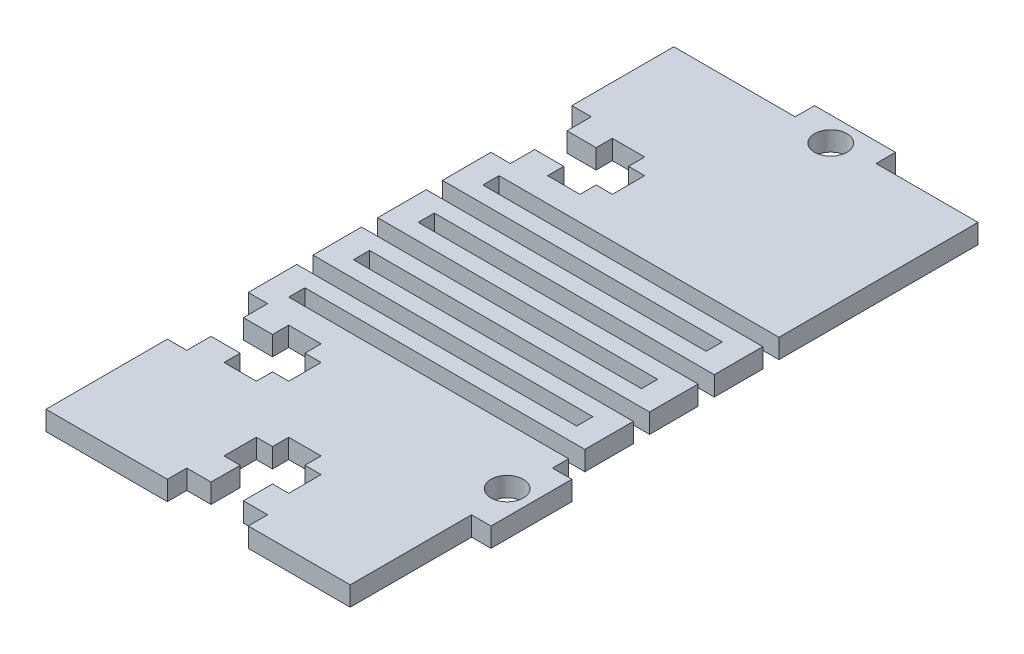
SolidWorks part; units mm, degrees
ref_plane "Front Plane" through (0, 0, 0) normal (0, 0, 1) x (1, 0, 0)
ref_plane "Top Plane" through (0, 0, 0) normal (0, 1, 0) x (1, 0, 0)
ref_plane "Right Plane" through (0, 0, 0) normal (1, 0, 0) x (0, 0, -1)
sketch "Sketch1" plane through (0, 0, 0) normal (0, 1, 0) x (1, 0, 0)
  line L1 (0, 0) -> (50.8, 0)
  line L2 (0, 0) -> (0, 50.8)
  line L3 (0, 50.8) -> (50.8, 50.8)
  line L4 (50.8, 0) -> (50.8, 50.8)
  line L5 (19.05, 50.8) -> (0, 50.8)
  line L6 (19.05, 50.8) -> (19.05, 47.752)
  line L7 (19.05, 47.752) -> (0, 47.752)
  line L8 (0, 50.8) -> (0, 47.752)
  line L9 (31.75, 50.8) -> (50.8, 50.8)
  line L10 (31.75, 50.8) -> (31.75, 47.752)
  line L11 (31.75, 47.752) -> (50.8, 47.752)
  line L12 (50.8, 50.8) -> (50.8, 47.752)
  line L13 (50.8, 50.8) -> (47.752, 50.8)
  line L14 (50.8, 50.8) -> (50.8, 31.75)
  line L15 (50.8, 31.75) -> (47.752, 31.75)
  line L16 (47.752, 50.8) -> (47.752, 31.75)
  line L17 (50.8, 0) -> (47.752, 0)
  line L18 (50.8, 0) -> (50.8, 19.05)
  line L19 (50.8, 19.05) -> (47.752, 19.05)
  line L20 (47.752, 0) -> (47.752, 19.05)
  line L21 (0, 19.05) -> (3.048, 19.05)
  line L22 (19.05, 0) -> (31.75, 0)
  line L23 (19.05, 0) -> (19.05, 3.048)
  line L24 (19.05, 3.048) -> (31.75, 3.048)
  line L25 (31.75, 0) -> (31.75, 3.048)
  line L26 (0, 19.05) -> (0, 31.75)
  line L27 (0, 31.75) -> (3.048, 31.75)
  line L28 (3.048, 19.05) -> (3.048, 31.75)
  point P25 (3.048, 25.4)
  dimension "D1" = 50.8
  dimension "D2" = 50.8
  dimension "D3" = 3.048
  dimension "D4" = 3.048
  dimension "D5" = 3.048
  dimension "D6" = 3.048
  dimension "D7" = 3.048
  dimension "D8" = 3.048
  dimension "D9" = 12.7
  dimension "D10" = 25.4
  dimension "D11" = 12.7
  dimension "D12" = 19.05
  dimension "D13" = 12.7
  dimension "D14" = 19.05
  dimension "D15" = 12.7
  dimension "D16" = 19.05
extrude "Boss-Extrude1" add sketch "Sketch1" along normal blind 3.048 contours L28 L21 L2 L1 L23 L24 L25 L20 L19 L4 L15 L16 L11 L10 L3 L6 L7 L27
sketch "Sketch2" plane through (0, 3.048, 0) normal (0, 1, 0) x (1, 0, 0)
  line L0 (3.048, 19.05) -> (3.048, 31.75) construction
  line L1 (3.048, 27.94) -> (15.24, 27.94)
  line L2 (3.048, 27.94) -> (3.048, 22.86)
  line L3 (3.048, 22.86) -> (15.24, 22.86)
  line L4 (15.24, 27.94) -> (15.24, 22.86)
  line L5 (19.05, 3.048) -> (31.75, 3.048) construction
  line L6 (7.62, 30.48) -> (12.7, 30.48)
  line L7 (7.62, 30.48) -> (7.62, 20.32)
  line L8 (7.62, 20.32) -> (12.7, 20.32)
  line L9 (12.7, 30.48) -> (12.7, 20.32)
  line L10 (22.86, 3.048) -> (27.94, 3.048)
  line L11 (22.86, 3.048) -> (22.86, 15.24)
  line L12 (22.86, 15.24) -> (27.94, 15.24)
  line L13 (27.94, 3.048) -> (27.94, 15.24)
  line L14 (19.05, 50.8) -> (31.75, 50.8) construction
  line L15 (20.32, 12.7) -> (30.48, 12.7)
  line L16 (20.32, 12.7) -> (20.32, 7.62)
  line L17 (20.32, 7.62) -> (30.48, 7.62)
  line L18 (30.48, 12.7) -> (30.48, 7.62)
  line L19 (19.05, 50.8) -> (19.05, 47.752) construction
  line L20 (50.8, 19.05) -> (47.752, 19.05) construction
  line L21 (50.8, 19.05) -> (50.8, 31.75) construction
  line L22 (0, 31.75) -> (0, 47.752) construction
  line L23 (0, 0) -> (19.05, 0) construction
  line L24 (0, 31.75) -> (3.048, 31.75) construction
  line L25 (19.05, 0) -> (19.05, 3.048) construction
  circle A0 centre (25.4, 46.99) radius 2.54
  circle A1 centre (46.99, 25.4) radius 2.54
  point P36 (25.4, 15.24)
  point P39 (3.048, 25.4)
  point P40 (12.7, 25.4)
  point P41 (25.4, 3.048)
  point P44 (25.4, 7.62)
  point P45 (20.32, 10.16)
  line M18 (3.048, 31.75) -> (3.048, 19.05)
  line M23 (19.05, 3.048) -> (31.75, 3.048)
  dimension "D5" = 5.08
  dimension "D6" = 5.08
  dimension "D1" = 3.81
  dimension "D2" = 6.35
  dimension "D3" = 6.35
  dimension "D4" = 3.81
  dimension "D7" = 15.24
  dimension "D8" = 15.24
  dimension "D9" = 5.08
  dimension "D10" = 5.08
  dimension "D11" = 6.35
  dimension "D12" = 6.35
  dimension "D13" = 6.35
  dimension "D14" = 6.35
  dimension "D15" = 10.16
  dimension "D16" = 10.16
  dimension "D17" = 5.08
  dimension "D18" = 5.08
  dimension "D19" = 2.54
  dimension "D20" = 2.54
extrude "Cut-Extrude1" cut sketch "Sketch2" against normal blind 3.048 contours L7 L1 L3 M18 | L9 L1 L7 L3 | L9 L6 L7 L1 | L1 L9 L3 L4 | L9 L3 L7 L8 | L11 L15 L13 L12 | L11 L17 L13 L15 | L18 L15 L13 L17 | L16 L17 L11 L15 | L17 L11 L13 M23 | A1 | A0
sketch "Sketch3" plane through (0, 3.048, 0) normal (0, 1, 0) x (1, 0, 0)
  line L1 (0, 31.75) -> (47.752, 31.75)
  line L2 (0, 31.75) -> (0, 69.85)
  line L3 (0, 69.85) -> (47.752, 69.85)
  line L4 (47.752, 31.75) -> (47.752, 69.85)
  line L5 (3.048, 69.85) -> (47.752, 69.85)
  line L6 (3.048, 69.85) -> (3.048, 82.55)
  line L7 (3.048, 82.55) -> (47.752, 82.55)
  line L8 (47.752, 69.85) -> (47.752, 82.55)
  line L9 (47.752, 82.55) -> (0, 82.55)
  line L10 (47.752, 82.55) -> (47.752, 98.552)
  line L11 (47.752, 98.552) -> (0, 98.552)
  line L12 (0, 82.55) -> (0, 98.552)
  line L13 (19.05, 98.552) -> (31.75, 98.552)
  line L14 (19.05, 98.552) -> (19.05, 101.6)
  line L15 (19.05, 101.6) -> (31.75, 101.6)
  line L16 (31.75, 98.552) -> (31.75, 101.6)
  point P15 (25.4, 101.6)
  line M38 (47.752, 47.752) -> (31.75, 47.752)
  line M39 (31.75, 47.752) -> (31.75, 50.8)
  line M40 (31.75, 50.8) -> (19.05, 50.8)
  line M41 (19.05, 50.8) -> (19.05, 47.752)
  line M42 (19.05, 47.752) -> (0, 47.752)
  dimension "D1" = 47.752
  dimension "D2" = 38.1
  dimension "D3" = 3.048
  dimension "D4" = 25.4
  dimension "D5" = 12.7
  dimension "D6" = 3.048
  dimension "D7" = 3.048
  dimension "D8" = 12.7
  dimension "D9" = 19.05
extrude "Boss-Extrude2" add sketch "Sketch3" against normal blind 3.048 contours L11 L16 L15 L14 | L12 L9 L7 L10 L11 | L3 L8 L7 L6 | L4 L3 L2 M38 M42 M41 M40 M39
sketch "Sketch4" plane through (0, 0, 0) normal (0, -1, 0) x (-1, 0, 0)
  circle A0 centre (-25.4, 46.99) radius 2.54
extrude "Boss-Extrude3" add sketch "Sketch4" against normal blind 3.048
sketch "Sketch5" plane through (0, 3.048, 0) normal (0, 1, 0) x (1, 0, 0)
  line L0 (3.048, 69.85) -> (3.048, 82.55) construction
  line L1 (3.048, 78.74) -> (15.24, 78.74)
  line L2 (3.048, 78.74) -> (3.048, 73.66)
  line L3 (3.048, 73.66) -> (15.24, 73.66)
  line L4 (15.24, 78.74) -> (15.24, 73.66)
  line L5 (19.05, 98.552) -> (19.05, 101.6) construction
  line L6 (12.7, 71.12) -> (7.62, 71.12)
  line L7 (12.7, 71.12) -> (12.7, 81.28)
  line L8 (12.7, 81.28) -> (7.62, 81.28)
  line L9 (7.62, 71.12) -> (7.62, 81.28)
  line L10 (19.05, 101.6) -> (31.75, 101.6) construction
  line L11 (3.048, 82.55) -> (0, 82.55) construction
  line L12 (0, 82.55) -> (0, 98.552) construction
  line L13 (47.752, 98.552) -> (47.752, 31.75) construction
  line L14 (47.752, 67.31) -> (3.81, 67.31)
  line L15 (47.752, 67.31) -> (47.752, 64.77)
  line L16 (47.752, 64.77) -> (3.81, 64.77)
  line L17 (3.81, 67.31) -> (3.81, 64.77)
  line L18 (0, 31.75) -> (0, 69.85) construction
  line L19 (0, 62.23) -> (43.942, 62.23)
  line L20 (0, 62.23) -> (0, 59.69)
  line L21 (0, 59.69) -> (43.942, 59.69)
  line L22 (43.942, 62.23) -> (43.942, 59.69)
  line L23 (0, 69.85) -> (3.048, 69.85) construction
  line L24 (47.752, 57.15) -> (3.81, 57.15)
  line L25 (47.752, 57.15) -> (47.752, 54.61)
  line L26 (47.752, 54.61) -> (3.81, 54.61)
  line L27 (3.81, 57.15) -> (3.81, 54.61)
  line L28 (0, 52.07) -> (43.942, 52.07)
  line L29 (0, 52.07) -> (0, 49.53)
  line L30 (0, 49.53) -> (43.942, 49.53)
  line L31 (43.942, 52.07) -> (43.942, 49.53)
  line L32 (47.752, 46.99) -> (3.81, 46.99)
  line L33 (47.752, 46.99) -> (47.752, 44.45)
  line L34 (47.752, 44.45) -> (3.81, 44.45)
  line L35 (3.81, 46.99) -> (3.81, 44.45)
  line L37 (0, 41.91) -> (43.942, 41.91)
  line L38 (0, 41.91) -> (0, 39.37)
  line L39 (0, 39.37) -> (43.942, 39.37)
  line L40 (43.942, 41.91) -> (43.942, 39.37)
  line L41 (47.752, 36.83) -> (3.81, 36.83)
  line L42 (47.752, 36.83) -> (47.752, 34.29)
  line L43 (47.752, 34.29) -> (3.81, 34.29)
  line L44 (3.81, 36.83) -> (3.81, 34.29)
  circle A0 centre (25.4, 97.79) radius 2.54
  point P16 (12.7, 76.2)
  point P19 (15.24, 76.2)
  line M29 (47.752, 31.75) -> (47.752, 98.552)
  line M37 (3.048, 82.55) -> (3.048, 69.85)
  line M39 (0, 69.85) -> (0, 31.75)
  dimension "D10" = 5.08
  dimension "D1" = 6.35
  dimension "D2" = 3.81
  dimension "D3" = 6.35
  dimension "D4" = 6.35
  dimension "D5" = 15.24
  dimension "D6" = 12.7
  dimension "D7" = 10.16
  dimension "D8" = 5.08
  dimension "D9" = 5.08
  dimension "D11" = 2.54
  dimension "D12" = 2.54
  dimension "D13" = 2.54
  dimension "D14" = 2.54
  dimension "D15" = 2.54
  dimension "D16" = 2.54
  dimension "D17" = 2.54
  dimension "D18" = 2.54
  dimension "D19" = 2.54
  dimension "D20" = 2.54
  dimension "D21" = 2.54
  dimension "D22" = 2.54
  dimension "D23" = 2.54
  dimension "D24" = 2.54
  dimension "D25" = 3.81
  dimension "D26" = 3.81
  dimension "D27" = 3.81
  dimension "D28" = 3.81
  dimension "D29" = 3.81
  dimension "D30" = 3.81
  dimension "D31" = 3.81
extrude "Cut-Extrude2" cut sketch "Sketch5" against normal through all contours A0 | L9 L1 L7 L8 | L3 L9 L1 M37 | L9 L3 L7 L1 | L7 L3 L4 L1 | L9 L6 L7 L3 | L14 L17 L16 M29 | L22 L19 L21 M39 | L24 L27 L26 M29 | L31 L28 L30 M39 | L32 L35 L34 M29 | L40 L37 L39 M39 | L41 L44 L43 M29
